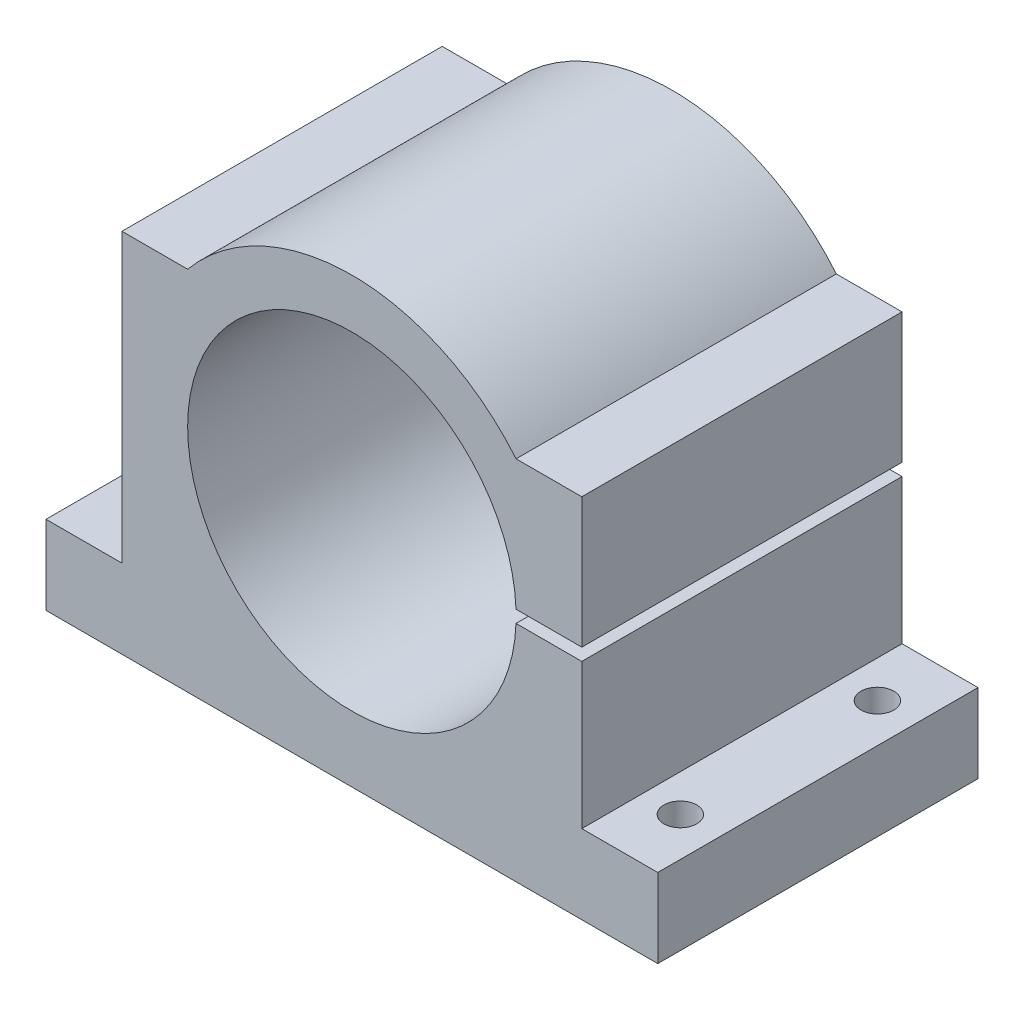
SolidWorks part; units mm, degrees
ref_plane "Front Plane" through (0, 0, 0) normal (0, 0, 1) x (1, 0, 0)
ref_plane "Top Plane" through (0, 0, 0) normal (0, 1, 0) x (1, 0, 0)
ref_plane "Right Plane" through (0, 0, 0) normal (1, 0, 0) x (0, 0, -1)
sketch "Sketch1" plane through (0, 0, 0) normal (0, 0, 1) x (1, 0, 0)
  line L0 (0, 19.2265) -> (18.5, 19.2265)
  line L1 (0, 0) -> (149, 0)
  line L2 (0, 0) -> (0, 19.2265)
  line L4 (149, 0) -> (149, 19.2265)
  line L5 (149, 19.2265) -> (130.5, 19.2265)
  line L6 (74.5, 108) -> (74.5, 0) construction
  line L7 (18.5, 19.2265) -> (18.5, 89.2265)
  line L8 (130.5, 19.2265) -> (130.5, 54.5)
  line L9 (18.5, 89.2265) -> (34.5, 89.2265)
  line L10 (130.5, 89.2265) -> (114.5, 89.2265)
  line L11 (74.5, 56) -> (130.5, 56) construction
  line L12 (130.5, 57.5) -> (114.4719, 57.5)
  line L13 (130.5, 54.5) -> (114.4719, 54.5)
  line L14 (123.44, 57.5) -> (123.44, 54.5) construction
  line L15 (130.5, 57.5) -> (130.5, 89.2265)
  arc A0 (114.4719, 57.5) -> (114.4719, 54.5) centre (74.5, 56) ccw
  arc A1 (34.5, 89.2265) -> (114.5, 89.2265) centre (74.5, 56) cw
  point P23 (123.44, 56)
  dimension "D1" = 80
  dimension "D7" = 12
  dimension "D8" = 12
  dimension "D2" = 149
  dimension "D3" = 108
  dimension "D4" = 70
  dimension "D5" = 80
  dimension "D6" = 112
  dimension "D9" = 3
extrude "Boss-Extrude1" add sketch "Sketch1" along normal blind 78
sketch "Sketch2" plane through (0, 0, 0) normal (0, -1, 0) x (1, 0, 0)
  line L0 (0, 63) -> (149, 63) construction
  line L1 (0, 78) -> (0, 0) construction
  line L2 (149, 78) -> (149, 0) construction
  line L3 (74.5, 78) -> (74.5, 0) construction
  line L4 (0, 78) -> (149, 78) construction
  line L5 (0, 0) -> (149, 0) construction
  line L6 (9.5, 78) -> (9.5, 0) construction
  line L7 (0, 15) -> (149, 15) construction
  circle A0 centre (9.5, 63) radius 4
  circle A2 centre (139.5, 63) radius 4
  circle A3 centre (9.5, 15) radius 4
  circle A4 centre (139.5, 15) radius 4
  dimension "D1" = 8
  dimension "D2" = 130
  dimension "D3" = 15
  dimension "D4" = 15
  dimension "D5" = 48
extrude "Cut-Extrude1" cut sketch "Sketch2" against normal through all
